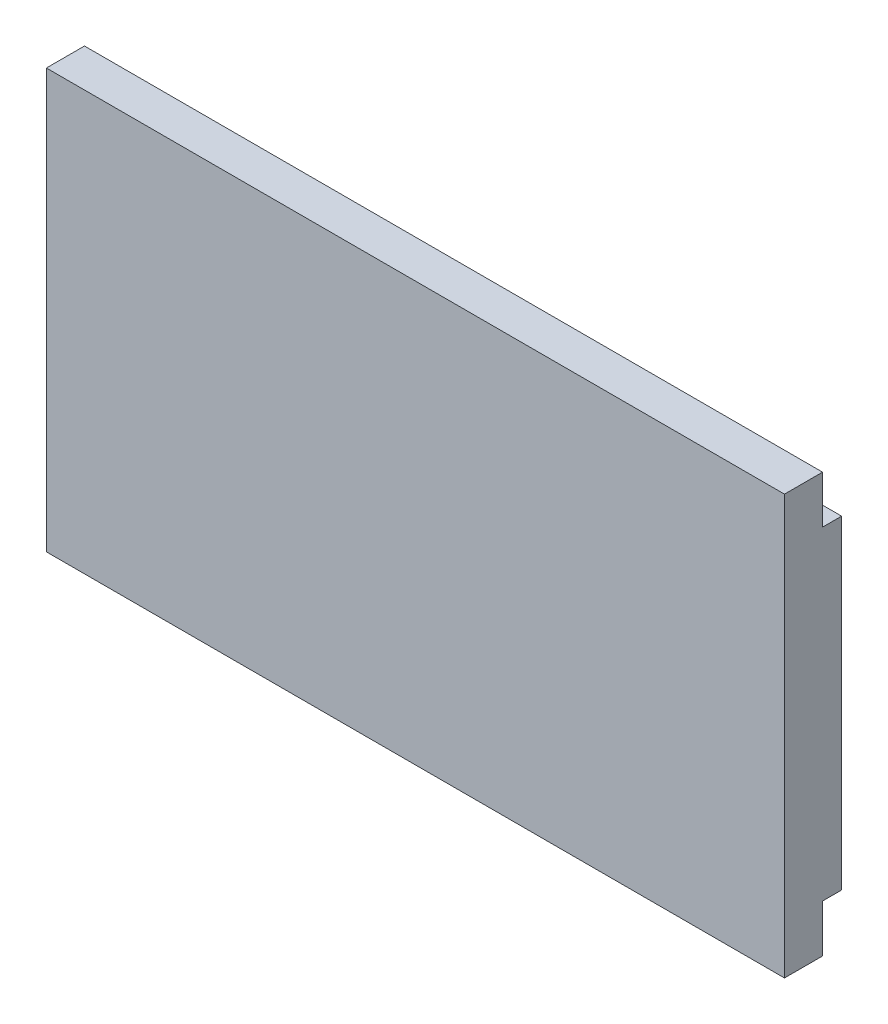
SolidWorks part; units mm, degrees
ref_plane "前视基准面" through (0, 0, 0) normal (0, 0, 1) x (1, 0, 0)
ref_plane "上视基准面" through (0, 0, 0) normal (0, 1, 0) x (1, 0, 0)
ref_plane "右视基准面" through (0, 0, 0) normal (1, 0, 0) x (0, 0, -1)
sketch "草图1" plane through (0, 0, 0) normal (0, 0, 1) x (1, 0, 0)
  line L1 (-15.5, 8.8) -> (15.5, 8.8)
  line L2 (-15.5, 8.8) -> (-15.5, -8.8)
  line L3 (-15.5, -8.8) -> (15.5, -8.8)
  line L4 (15.5, 8.8) -> (15.5, -8.8)
  line L5 (-15.5, 8.8) -> (15.5, -8.8) construction
  line L6 (-15.5, -8.8) -> (15.5, 8.8) construction
  point P1 (0, 0)
  dimension "D1" = 17.6
  dimension "D2" = 31
extrude "凸台-拉伸1" add sketch "草图1" along normal blind 1.6
sketch "草图2" plane through (0, 0, 0) normal (0, 0, -1) x (-1, 0, 0)
  line L0 (-13.5, -8.8) -> (-13.5, -6.8)
  line L1 (15.5, -8.8) -> (-15.5, -8.8) construction
  line L2 (-13.5, -6.8) -> (-15.5, -6.8)
  line L3 (-15.5, -8.8) -> (-15.5, 8.8) construction
  line L4 (-15.5, -6.8) -> (-15.5, 6.8)
  line L5 (-15.5, 6.8) -> (-1, 6.8)
  line L6 (-1, 6.8) -> (-1, 4.8)
  line L7 (-1, 4.8) -> (3, 4.8)
  line L8 (3, 4.8) -> (3, 6.7352)
  line L9 (3, 6.7352) -> (15.5, 6.7352)
  line L10 (15.5, 8.8) -> (15.5, -8.8) construction
  line L11 (15.5, 6.7352) -> (15.5, -6.8)
  line L12 (15.5, -6.8) -> (13.5, -6.8)
  line L13 (13.5, -6.8) -> (13.5, -8.8)
  line L14 (13.5, -8.8) -> (-13.5, -8.8)
  dimension "D1" = 2
  dimension "D2" = 2
  dimension "D3" = 2
  dimension "D4" = 2
  dimension "D5" = 2
  dimension "D6" = 4
  dimension "D7" = 13.6
  dimension "D8" = 14.5
extrude "凸台-拉伸2" add sketch "草图2" along normal blind 0.8
